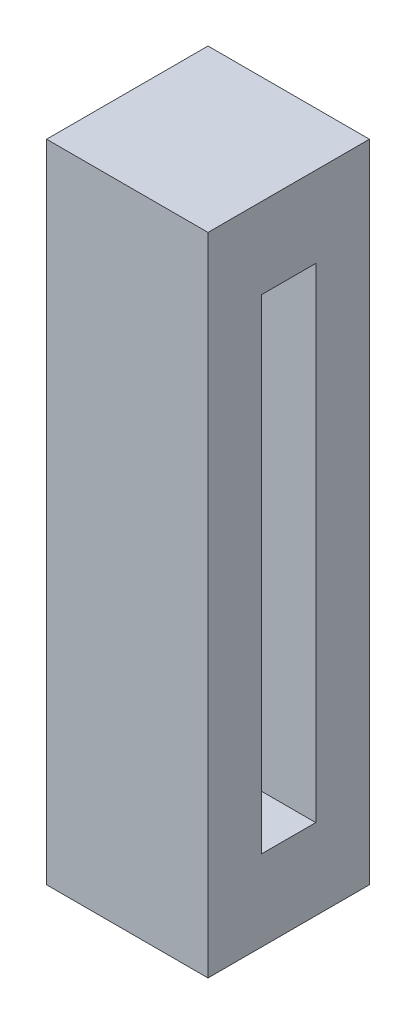
SolidWorks part; units mm, degrees
material "Brass"
ref_plane "Front Plane" through (0, 0, 0) normal (0, 0, 1) x (1, 0, 0)
ref_plane "Top Plane" through (0, 0, 0) normal (0, 1, 0) x (1, 0, 0)
ref_plane "Right Plane" through (0, 0, 0) normal (1, 0, 0) x (0, 0, -1)
sketch "Sketch1" plane through (0, 0, 0) normal (0, 0, 1) x (1, 0, 0)
  line L1 (-1, -4) -> (1, -4)
  line L2 (-1, -4) -> (-1, 4)
  line L3 (-1, 4) -> (1, 4)
  line L4 (1, -4) -> (1, 4)
  line L5 (-1, -4) -> (1, 4) construction
  line L6 (-1, 4) -> (1, -4) construction
  point P0 (0, 0)
  dimension "D1" = 8
  dimension "D2" = 2
extrude "Boss-Extrude1" add sketch "Sketch1" along normal blind 2
sketch "Sketch2" plane through (-1, 0, 0) normal (-1, 0, 0) x (0, 0, 1)
  line L0 (0, 4) -> (2, -4) construction
  line L1 (0.665, -3) -> (1.335, -3)
  line L2 (0.665, -3) -> (0.665, 3)
  line L3 (0.665, 3) -> (1.335, 3)
  line L4 (1.335, -3) -> (1.335, 3)
  line L5 (0.665, -3) -> (1.335, 3) construction
  line L6 (0.665, 3) -> (1.335, -3) construction
  point P0 (1, 0)
  point P9 (0, 0)
  point P10 (1, 0)
  dimension "D1" = 0.67
  dimension "D2" = 6
extrude "Cut-Extrude1" cut sketch "Sketch2" against normal blind 3
